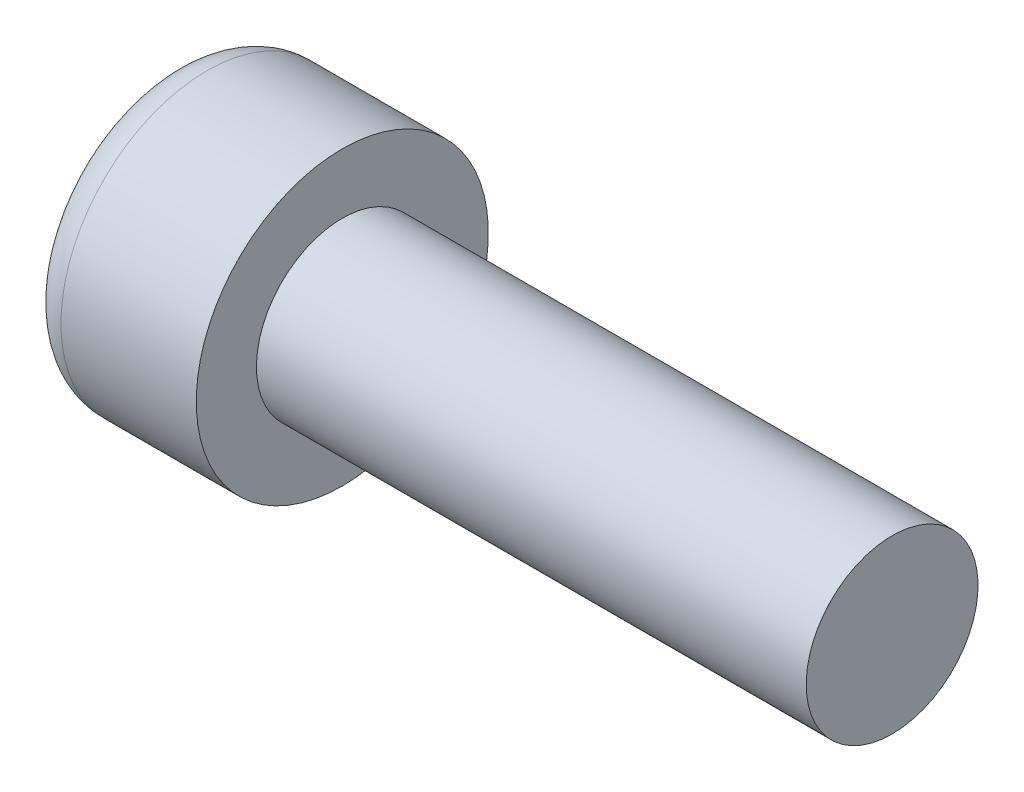
SolidWorks part; units mm, degrees
material "Plain Carbon Steel"
ref_plane "Front Plane" through (0, 0, 0) normal (0, 0, 1) x (1, 0, 0)
ref_plane "Top Plane" through (0, 0, 0) normal (0, 1, 0) x (1, 0, 0)
ref_plane "Right Plane" through (0, 0, 0) normal (1, 0, 0) x (0, 0, -1)
sketch "Sketch1" plane through (0, 0, 0) normal (0, 0, 1) x (1, 0, 0)
  line L0 (0, 0) -> (0, 3.1875)
  line L1 (1.0625, 4.25) -> (5, 4.25)
  line L2 (5, 4.25) -> (5, 2.5)
  line L3 (5, 2.5) -> (21, 2.5)
  line L4 (21, 2.5) -> (21, 0)
  line L5 (21, 0) -> (0, 0) construction
  line L6 (1.0625, 3.1875) -> (1.0625, 2.125) construction
  line L7 (1.0625, 2.125) -> (1.0625, 1.0625) construction
  line L8 (1.0625, 1.0625) -> (1.0625, 0) construction
  line L9 (1.0625, 4.25) -> (1.0625, 3.1875) construction
  line L10 (0, 0) -> (21, 0)
  arc A0 (0, 3.1875) -> (1.0625, 4.25) centre (1.0625, 3.1875) cw
  dimension "D1" = 5
  dimension "D2" = 8.5
  dimension "D3" = 5
  dimension "D4" = 16
revolve "Revolve1" add sketch "Sketch1" angle 360 about L10
sketch "Sketch2" plane through (0, 0, 0) normal (-1, 0, 0) x (0, 0, 1)
  line L1 (0, 2.3094) -> (-2, 1.1547)
  line L2 (-2, 1.1547) -> (-2, -1.1547)
  line L3 (-2, -1.1547) -> (0, -2.3094)
  line L4 (0, -2.3094) -> (2, -1.1547)
  line L5 (2, -1.1547) -> (2, 1.1547)
  line L6 (2, 1.1547) -> (0, 2.3094)
  circle A0 centre (0, 0) radius 2 construction
  dimension "D1" = 4
extrude "Cut-Extrude1" cut sketch "Sketch2" against normal blind 2.5
